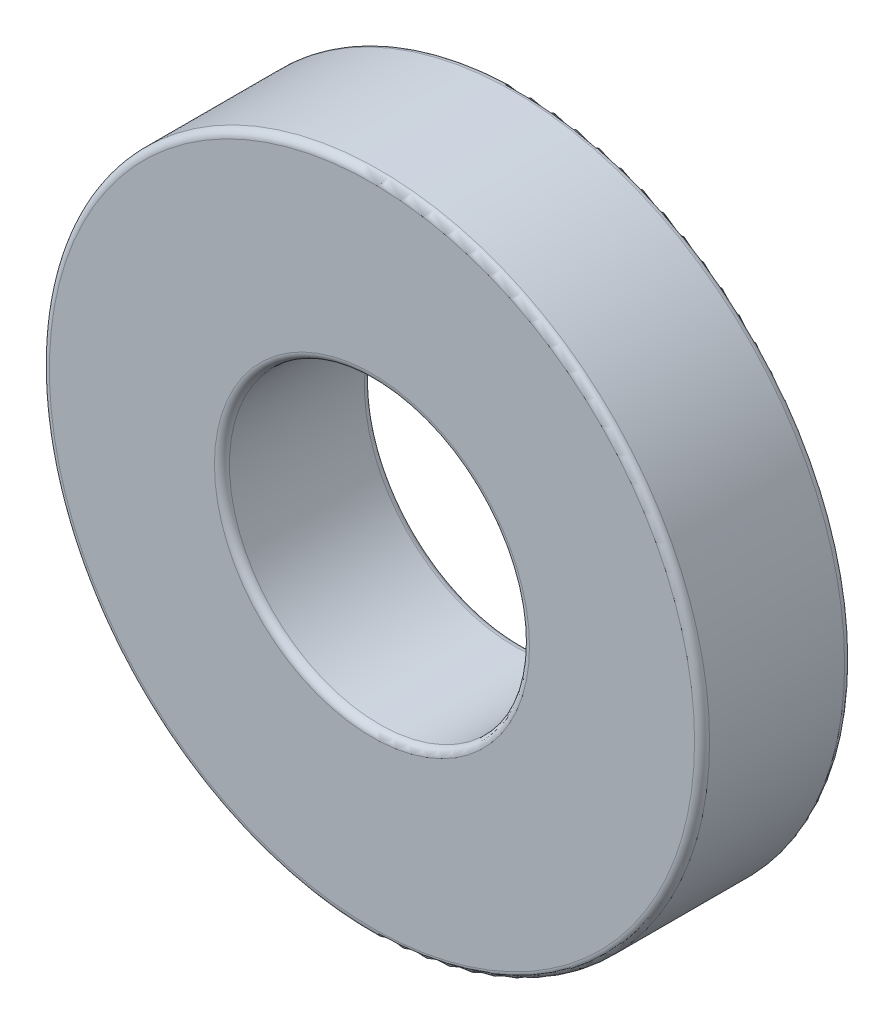
SolidWorks part; units mm, degrees
ref_plane "Front Plane" through (0, 0, 0) normal (0, 0, 1) x (1, 0, 0)
ref_plane "Top Plane" through (0, 0, 0) normal (0, 1, 0) x (1, 0, 0)
ref_plane "Right Plane" through (0, 0, 0) normal (1, 0, 0) x (0, 0, -1)
sketch "Sketch1" plane through (0, 0, 0) normal (0, 0, 1) x (1, 0, 0)
  circle A0 centre (0, 0) radius 2.2
  circle A1 centre (0, 0) radius 1
  dimension "D1" = 4.4
  dimension "D2" = 2
extrude "Boss-Extrude1" add sketch "Sketch1" along normal blind 1
fillet "Fillet1" radius 0.05 4 edges at (1, 0, 0) (1, 0, 1) (2.2, 0, 0) (2.2, 0, 1)
